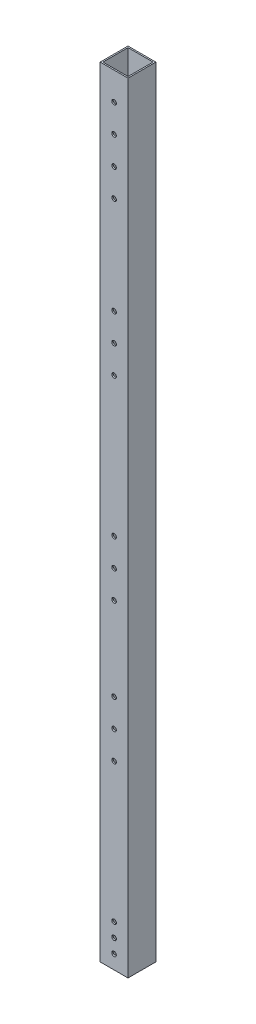
SolidWorks part; units mm, degrees
ref_plane "前视基准面" through (0, 0, 0) normal (0, 0, 1) x (1, 0, 0)
ref_plane "上视基准面" through (0, 0, 0) normal (0, 1, 0) x (1, 0, 0)
ref_plane "右视基准面" through (0, 0, 0) normal (1, 0, 0) x (0, 0, -1)
other "Configuration Table"
sketch "草图1" plane through (0, 0, 0) normal (0, 1, 0) x (1, 0, 0)
  line L9 (-9, 9) -> (9, 9)
  line L10 (-9, 9) -> (-9, -9)
  line L11 (-9, -9) -> (9, -9)
  line L12 (9, 9) -> (9, -9)
  line L13 (-9, 9) -> (9, -9) construction
  line L14 (-9, -9) -> (9, 9) construction
  line L15 (-10, 10) -> (10, 10)
  line L16 (-10, 10) -> (-10, -10)
  line L17 (-10, -10) -> (10, -10)
  line L18 (10, 10) -> (10, -10)
  line L19 (-10, 10) -> (10, -10) construction
  line L20 (-10, -10) -> (10, 10) construction
  point P0 (0, 0)
  point P6 (0, 0)
  dimension "D1" = 18
  dimension "D2" = 18
  dimension "D3" = 20
  dimension "D4" = 20
extrude "凸台-拉伸1" add sketch "草图1" along normal blind 740
sketch "草图3" plane through (0, 0, 10) normal (0, 0, 1) x (1, 0, 0)
  line L0 (0, 740) -> (0, 720) construction
  line L1 (-10, 740) -> (10, 740) construction
  line L2 (0, 720) -> (0, 700) construction
  line L3 (0, 700) -> (0, 680) construction
  line L4 (0, 680) -> (0, 660) construction
  circle A0 centre (0, 720) radius 1.65
  circle A1 centre (0, 700) radius 1.65
  circle A2 centre (0, 680) radius 1.65
  circle A3 centre (0, 660) radius 1.65
  circle A4 centre (0, 590) radius 1.65
  circle A5 centre (0, 570) radius 1.65
  circle A6 centre (0, 550) radius 1.65
  circle A10 centre (0, 450) radius 1.65
  circle A11 centre (0, 430) radius 1.65
  circle A12 centre (0, 410) radius 1.65
  dimension "D5" = 3.3
  dimension "D6" = 3.3
  dimension "D7" = 3.3
  dimension "D8" = 3.3
  dimension "D10" = 3.3
  dimension "D13" = 3.3
  dimension "D14" = 3.3
  dimension "D18" = 3.3
  dimension "D19" = 3.3
  dimension "D20" = 3.3
  dimension "D1" = 20
  dimension "D2" = 20
  dimension "D3" = 20
  dimension "D4" = 20
  dimension "D9" = 150
  dimension "D11" = 20
  dimension "D12" = 20
  dimension "D15" = 100
  dimension "D16" = 20
  dimension "D17" = 20
extrude "切除-拉伸1" cut sketch "草图3" against normal blind 32
sketch "草图5" plane through (0, 0, 0) normal (0, -1, 0) x (1, 0, 0)
  circle A0 centre (0, 0) radius 15.3974
extrude "切除-拉伸2" cut sketch "草图5" against normal blind 180
sketch "草图7" plane through (0, 0, 10) normal (0, 0, 1) x (1, 0, 0)
  line L0 (0, 180) -> (0, 190) construction
  line L1 (10, 180) -> (-10, 180) construction
  circle A1 centre (0, 190) radius 1.65
  circle A2 centre (0, 200) radius 1.65
  circle A3 centre (0, 210) radius 1.65
  circle A4 centre (0, 310) radius 1.65
  circle A5 centre (0, 330) radius 1.65
  circle A6 centre (0, 350) radius 1.65
  dimension "D1" = 3.3
  dimension "D5" = 3.3
  dimension "D3" = 10
  dimension "D4" = 10
  dimension "D6" = 130
  dimension "D2" = 3
  dimension "D7" = 3
extrude "切除-拉伸3" cut sketch "草图7" against normal blind 40 from offset 0
equation "\"3，3\"=4.75023"
